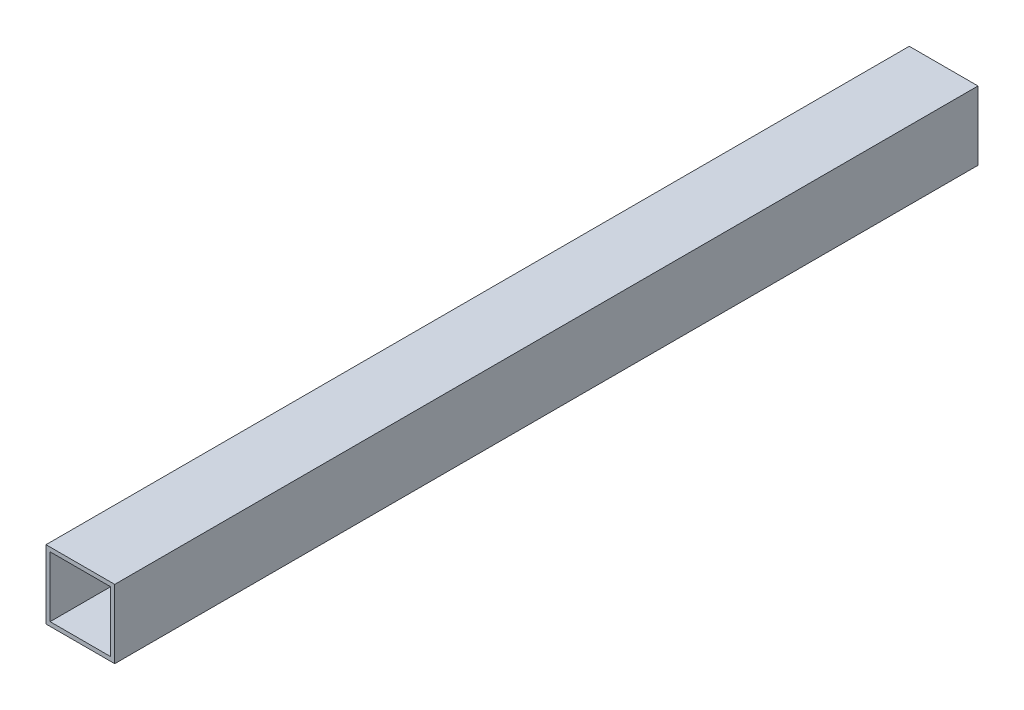
SolidWorks part; units mm, degrees
ref_plane "Front" through (0, 0, 0) normal (0, 0, 1) x (1, 0, 0)
ref_plane "Top" through (0, 0, 0) normal (0, 1, 0) x (1, 0, 0)
ref_plane "Right" through (0, 0, 0) normal (1, 0, 0) x (0, 0, -1)
sketch "Эскиз1" plane through (0, 0, 0) normal (0, 0, 1) x (1, 0, 0)
  line L1 (-12.5, -12.5) -> (12.5, -12.5)
  line L2 (-12.5, -12.5) -> (-12.5, 12.5)
  line L3 (-12.5, 12.5) -> (12.5, 12.5)
  line L4 (12.5, -12.5) -> (12.5, 12.5)
  line L5 (-12.5, -12.5) -> (12.5, 12.5) construction
  line L6 (-12.5, 12.5) -> (12.5, -12.5) construction
  point P0 (0, 0)
  dimension "D1" = 25
  dimension "D2" = 25
extrude "Вытянуть-Тонкостенный1" add sketch "Эскиз1" along normal blind 314 thin thin type one direction reverse wall 1.5
